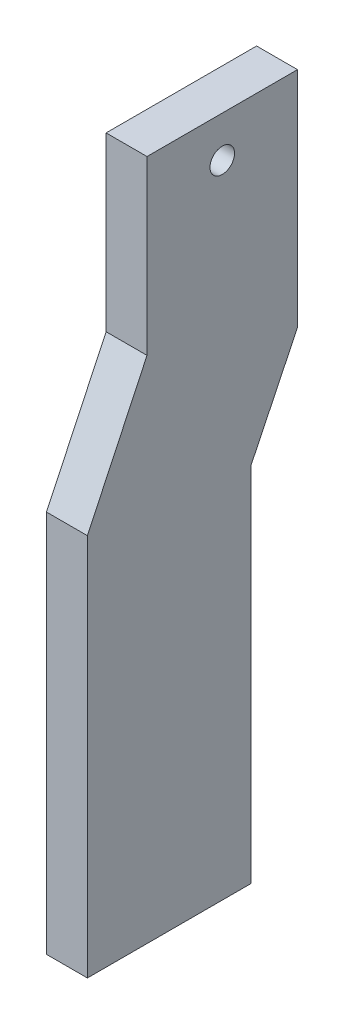
SolidWorks part; units mm, degrees
ref_plane "Спереди" through (0, 0, 0) normal (0, 0, 1) x (1, 0, 0)
ref_plane "Сверху" through (0, 0, 0) normal (0, 1, 0) x (1, 0, 0)
ref_plane "Справа" through (0, 0, 0) normal (1, 0, 0) x (0, 0, -1)
sketch "Эскиз1" plane through (0, 0, 0) normal (1, 0, 0) x (0, 0, -1)
  line L0 (-19.9999, 63.4837) -> (-5.4307, 94.3588)
  line L1 (20.0001, 58.3956) -> (31.3539, 81.8971)
  line L2 (-19.9999, 63.4837) -> (-19.9999, -30.1439)
  line L3 (-19.9999, -30.1439) -> (20.0001, -30.1439)
  line L4 (20.0001, 58.3956) -> (20.0001, -30.1439)
  line L5 (-5.4307, 94.3588) -> (-5.4307, 136.4532)
  line L6 (40.9616, 134.4532) -> (-15.0384, 134.4532) construction
  line L7 (-5.4307, 136.4532) -> (31.3539, 136.4532)
  line L8 (31.3539, 136.4532) -> (31.3539, 81.8971)
  point P22 (8.6411, 134.4532)
  dimension "D1" = 40
extrude "Вытянуть1" add sketch "Эскиз1" along normal blind 10
sketch "Эскиз2" plane through (0, 0, 0) normal (-1, 0, 0) x (0, 0, 1)
  circle A2 centre (-12.9616, 126.4532) radius 3
extrude "Вырез-Вытянуть1" cut sketch "Эскиз2" against normal blind 25
